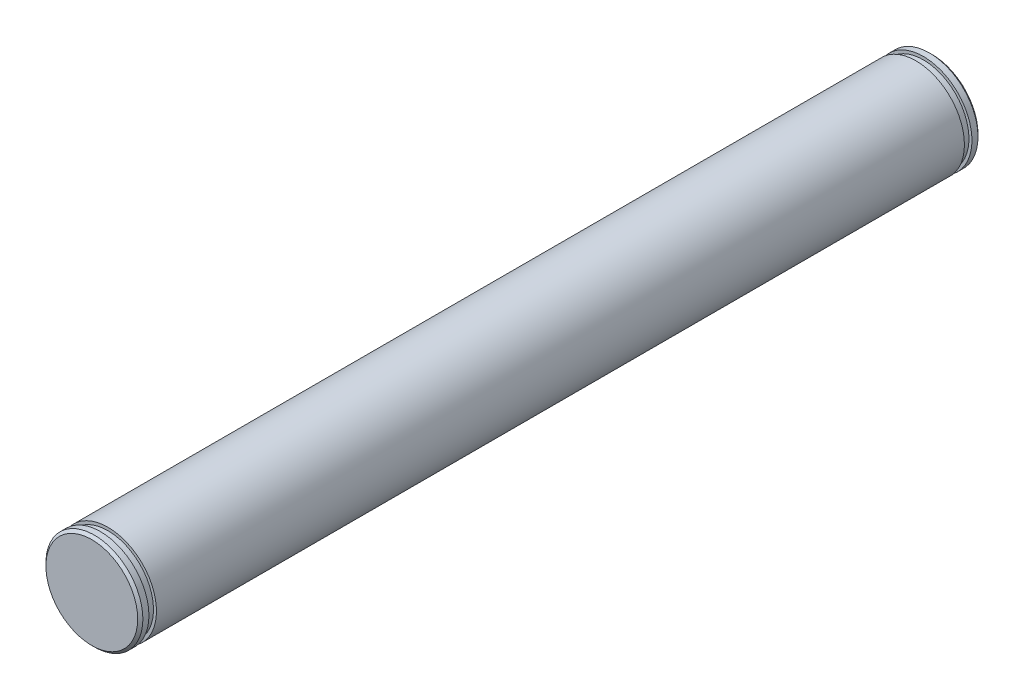
SolidWorks part; units mm, degrees
material "AISI 1020 Steel, Cold Rolled"
ref_plane "Front Plane" through (0, 0, 0) normal (0, 0, 1) x (1, 0, 0)
ref_plane "Top Plane" through (0, 0, 0) normal (0, 1, 0) x (1, 0, 0)
ref_plane "Right Plane" through (0, 0, 0) normal (1, 0, 0) x (0, 0, -1)
sketch "Sketch1" plane through (0, 0, 0) normal (0, 0, 1) x (1, 0, 0)
  circle A0 centre (0, 0) radius 4.7625
  dimension "D1" = 9.525
extrude "Boss-Extrude1" add sketch "Sketch1" along normal mid plane 82.55
sketch "Sketch2" plane through (0, 0, 0) normal (1, 0, 0) x (0, 0, -1)
  line L0 (0, 0) -> (-30.229, 0) construction
  line L1 (-40.4241, 7.0104) -> (-39.6875, 7.0104)
  line L2 (-40.4241, 7.0104) -> (-40.4241, 4.4704)
  line L3 (-40.4241, 4.4704) -> (-39.6875, 4.4704)
  line L4 (-39.6875, 7.0104) -> (-39.6875, 4.4704)
  dimension "D1" = 0.7366
  dimension "D2" = 39.6875
  dimension "D3" = 8.9408
  dimension "D4" = 2.54
revolve "Cut-Revolve1" cut sketch "Sketch2" angle 360 about L0
chamfer "Chamfer1" distance 0.254 angle 45 2 edges at (4.7625, 0, 41.275) (4.7625, 0, -41.275)
mirror "Mirror3" about plane through (0, 0, 0) normal (0, 0, 1) of "Cut-Revolve1"
